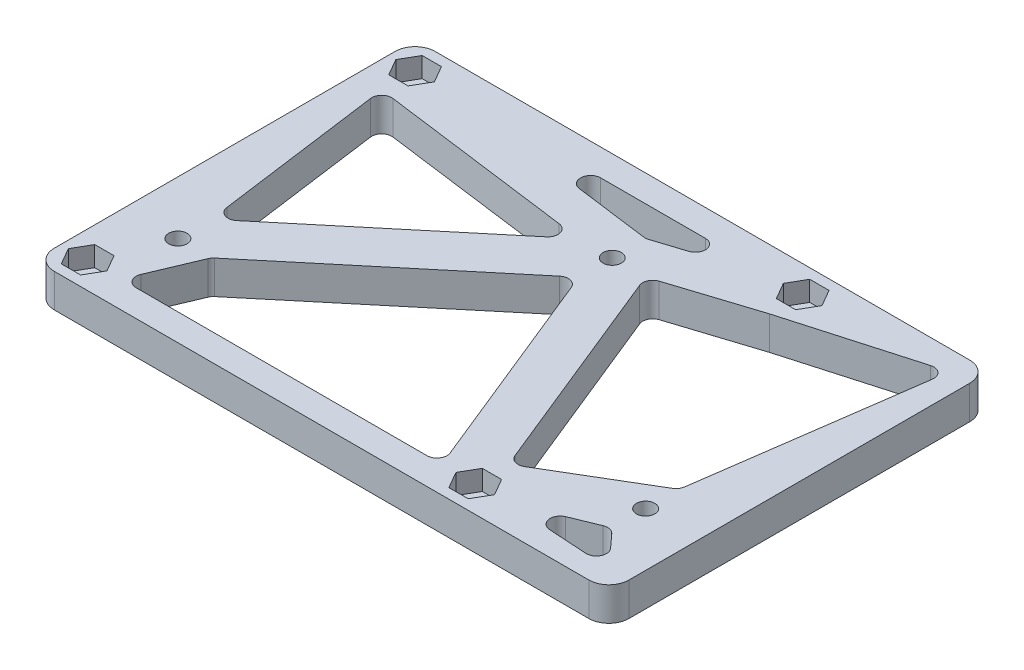
SolidWorks part; units mm, degrees
ref_plane "Front Plane" through (0, 0, 0) normal (0, 0, 1) x (1, 0, 0)
ref_plane "Top Plane" through (0, 0, 0) normal (0, 1, 0) x (1, 0, 0)
ref_plane "Right Plane" through (0, 0, 0) normal (1, 0, 0) x (0, 0, -1)
sketch "Sketch1" plane through (0, 0, 0) normal (0, 1, 0) x (1, 0, 0)
  line L0 (-37.0529, 19.2423) -> (-8.392, 15.4489)
  line L1 (-40, -28.5) -> (40, -28.5)
  line L2 (-43, -25.5) -> (-43, 25.5)
  line L3 (-40, 28.5) -> (40, 28.5)
  line L4 (43, -25.5) -> (43, 25.5)
  line L5 (-7.6285, 12.8096) -> (-32.9176, -8.2646)
  line L6 (-35.3642, -7.3138) -> (-38.7361, 17.5537)
  line L7 (-1.5779, 8.6851) -> (-29.7195, -14.7663)
  line L8 (-30.1417, -15.3365) -> (-33.1233, -22.4179)
  line L9 (-31.7409, -24.5) -> (11.7725, -24.5)
  line L10 (13.1624, -22.436) -> (0.7723, 8.0968)
  line L11 (-11.2345, 24.5) -> (4.4315, 24.5)
  line L12 (4.8905, 21.572) -> (0.3213, 20.1033)
  line L13 (-0.3345, 20.0443) -> (-11.4313, 21.513)
  line L14 (6.5386, 15.4945) -> (19, 19.5)
  line L15 (19, 19.5) -> (37.7807, 24.8659)
  line L16 (39.6781, 23.2144) -> (35.1004, -9.287)
  line L17 (34.3809, -10.3676) -> (20.4998, -18.6095)
  line L18 (18.3441, -17.8837) -> (5.6077, 13.5025)
  line L19 (30.0556, -22.0227) -> (34.0283, -20.3975)
  line L20 (35.7062, -20.7768) -> (37.512, -22.7632)
  line L21 (36.3085, -25.2693) -> (30.5299, -24.9081)
  line L22 (-39, 24.5) -> (-39, 19.5) construction
  line L23 (-39, 24.5) -> (-34, 24.5) construction
  line L24 (-39, -24.5) -> (-34, -24.5) construction
  line L25 (-35, -15) -> (-30, -15) construction
  line L26 (-35, -15) -> (-35, -10) construction
  line L27 (-5, 15) -> (0, 15) construction
  line L28 (0, 15) -> (0, 20) construction
  line L29 (0, 15) -> (5, 15) construction
  line L30 (0, 15) -> (0, 10) construction
  line L31 (14, 24.5) -> (19, 24.5) construction
  line L32 (19, 24.5) -> (19, 19.5) construction
  line L33 (19, -24.5) -> (14, -24.5) construction
  line L34 (19, -19.5) -> (19, -24.5) construction
  line L35 (19, -24.5) -> (24, -24.5) construction
  line L36 (35, -15) -> (35, -20) construction
  line L37 (35, -15) -> (35, -10) construction
  arc A0 (40, 28.5) -> (43, 25.5) centre (40, 25.5) cw
  arc A1 (40, -28.5) -> (43, -25.5) centre (40, -25.5) ccw
  arc A2 (-40, -28.5) -> (-43, -25.5) centre (-40, -25.5) cw
  arc A3 (-43, 25.5) -> (-40, 28.5) centre (-40, 25.5) cw
  circle A4 centre (0, 15) radius 1.375
  circle A5 centre (-35, -15) radius 1.375
  circle A6 centre (35, -15) radius 1.375
  circle A7 centre (-39, 24.5) radius 1.375
  circle A8 centre (19, 24.5) radius 1.375
  circle A9 centre (19, -24.5) radius 1.375
  circle A10 centre (-39, -24.5) radius 1.375
  arc A11 (37.512, -22.7632) -> (36.3085, -25.2693) centre (36.4021, -23.7722) cw
  arc A12 (35.7062, -20.7768) -> (34.0283, -20.3975) centre (34.5963, -21.7858) ccw
  arc A13 (30.5299, -24.9081) -> (30.0556, -22.0227) centre (30.6235, -23.411) cw
  arc A14 (39.6781, 23.2144) -> (37.7807, 24.8659) centre (38.1927, 23.4236) ccw
  arc A15 (20.4998, -18.6095) -> (18.3441, -17.8837) centre (19.734, -17.3197) cw
  arc A16 (5.6077, 13.5025) -> (6.5386, 15.4945) centre (6.9976, 14.0665) cw
  arc A17 (0.3213, 20.1033) -> (-0.3345, 20.0443) centre (-0.1377, 21.5313) cw
  arc A18 (4.8905, 21.572) -> (4.4315, 24.5) centre (4.4315, 23) ccw
  arc A19 (-11.4313, 21.513) -> (-11.2345, 24.5) centre (-11.2345, 23) cw
  arc A20 (0.7723, 8.0968) -> (-1.5779, 8.6851) centre (-0.6176, 7.5328) ccw
  arc A21 (13.1624, -22.436) -> (11.7725, -24.5) centre (11.7725, -23) cw
  arc A22 (-31.7409, -24.5) -> (-33.1233, -22.4179) centre (-31.7409, -23) cw
  arc A23 (-30.1417, -15.3365) -> (-29.7195, -14.7663) centre (-28.7592, -15.9186) cw
  arc A24 (-32.9176, -8.2646) -> (-35.3642, -7.3138) centre (-33.8778, -7.1123) cw
  arc A25 (-7.6285, 12.8096) -> (-8.392, 15.4489) centre (-8.5888, 13.9619) ccw
  arc A26 (-37.0529, 19.2423) -> (-38.7361, 17.5537) centre (-37.2497, 17.7553) ccw
  arc A27 (34.3809, -10.3676) -> (35.1004, -9.287) centre (33.6151, -9.0778) ccw
  point P4 (0, -28.5)
  point P6 (-43, 0)
  point P9 (43, 28.5)
  point P12 (43, -28.5)
  point P17 (-43, 28.5)
  point P32 (-39, 19.5)
  point P33 (-35, -10)
  point P34 (-5, 15)
  point P35 (-34, 24.5)
  point P36 (14, 24.5)
  point P37 (0, 20)
  point P38 (-34, -24.5)
  point P39 (-30, -15)
  point P40 (0, 10)
  point P41 (14, -24.5)
  point P42 (5, 15)
  point P43 (19, 19.5)
  point P44 (35, -10)
  point P45 (40, 25.5)
  point P46 (19, -19.5)
  point P59 (24, -24.5)
  point P62 (35, -20)
  point P64 (40, -25.5)
  dimension "D3" = 3
  dimension "D5" = 2.75
  dimension "D13" = 2.75
  dimension "D15" = 1.5
  dimension "D16" = 1.5
  dimension "D1" = 86
  dimension "D2" = 57
  dimension "D4" = 70
  dimension "D6" = 35
  dimension "D7" = 15
  dimension "D8" = 15
  dimension "D9" = 58
  dimension "D10" = 49
  dimension "D11" = 4
  dimension "D12" = 4
  dimension "D14" = 5
extrude "Boss-Extrude1" add sketch "Sketch1" along normal blind 5
sketch "Sketch2" plane through (0, 5, 0) normal (0, 1, 0) x (1, 0, 0)
  line L0 (40, 28.5) -> (-40, 28.5) construction
  line L1 (-36.1132, 24.5) -> (-37.5566, 27)
  line L2 (-37.5566, 27) -> (-40.4434, 27)
  line L3 (-40.4434, 27) -> (-41.8868, 24.5)
  line L4 (-41.8868, 24.5) -> (-40.4434, 22)
  line L5 (-40.4434, 22) -> (-37.5566, 22)
  line L6 (-37.5566, 22) -> (-36.1132, 24.5)
  line L7 (20.4434, 27) -> (17.5566, 27)
  line L8 (17.5566, 27) -> (16.1132, 24.5)
  line L9 (16.1132, 24.5) -> (17.5566, 22)
  line L10 (17.5566, 22) -> (20.4434, 22)
  line L11 (20.4434, 22) -> (21.8868, 24.5)
  line L12 (21.8868, 24.5) -> (20.4434, 27)
  line L13 (20.4434, -22) -> (17.5566, -22)
  line L14 (17.5566, -22) -> (16.1132, -24.5)
  line L15 (16.1132, -24.5) -> (17.5566, -27)
  line L16 (17.5566, -27) -> (20.4434, -27)
  line L17 (20.4434, -27) -> (21.8868, -24.5)
  line L18 (21.8868, -24.5) -> (20.4434, -22)
  line L19 (-36.1132, -24.5) -> (-37.5566, -22)
  line L20 (-37.5566, -22) -> (-40.4434, -22)
  line L21 (-40.4434, -22) -> (-41.8868, -24.5)
  line L22 (-41.8868, -24.5) -> (-40.4434, -27)
  line L23 (-40.4434, -27) -> (-37.5566, -27)
  line L24 (-37.5566, -27) -> (-36.1132, -24.5)
  circle A7 centre (-39, 24.5) radius 2.5 construction
  circle A8 centre (19, 24.5) radius 2.5 construction
  circle A9 centre (19, -24.5) radius 2.5 construction
  circle A10 centre (-39, -24.5) radius 2.5 construction
  dimension "D1" = 5
extrude "Cut-Extrude1" cut sketch "Sketch2" against normal blind 3
sketch "Sketch3" plane through (0, 0, 0) normal (0, -1, 0) x (1, 0, 0)
  circle A4 centre (-35, 15) radius 2.5
  circle A5 centre (35, 15) radius 2.5
  circle A6 centre (0, -15) radius 2.5
  dimension "D1" = 5
extrude "Cut-Extrude2" cut sketch "Sketch3" against normal blind 2.5
